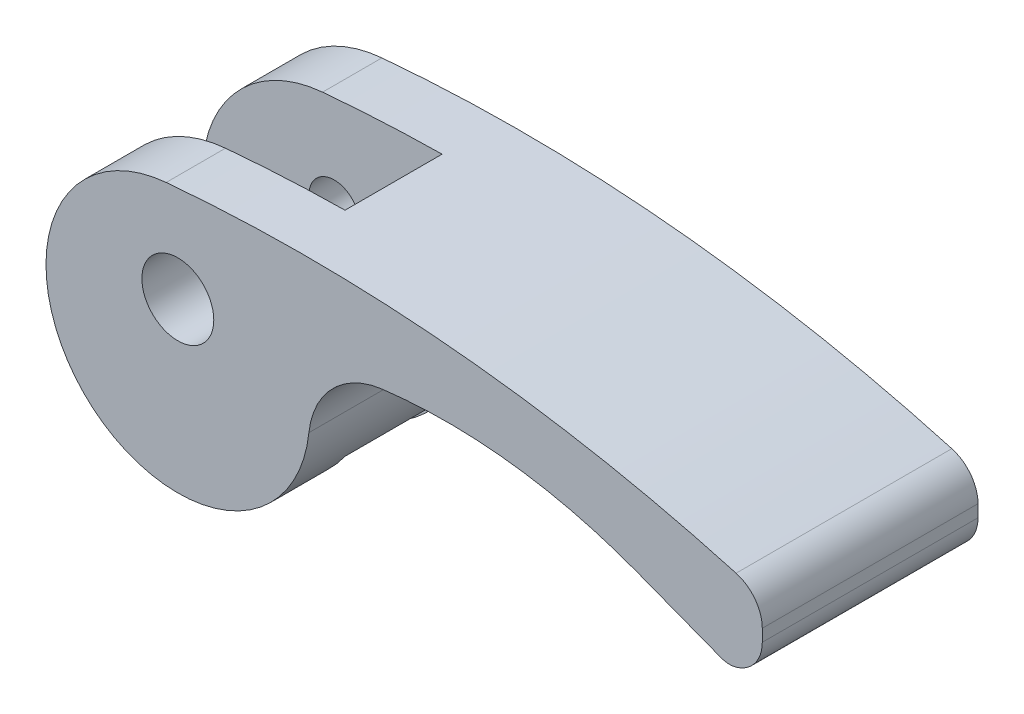
SolidWorks part; units mm, degrees
ref_plane "Спереди" through (0, 0, 0) normal (0, 0, 1) x (1, 0, 0)
ref_plane "Сверху" through (0, 0, 0) normal (0, 1, 0) x (1, 0, 0)
ref_plane "Справа" through (0, 0, 0) normal (1, 0, 0) x (0, 0, -1)
sketch "Эскиз1" plane through (0, 0, 0) normal (0, 0, 1) x (1, 0, 0)
  circle A0 centre (0, 0) radius 11
  dimension "D1" = 22
extrude "Бобышка-Вытянуть1" add sketch "Эскиз1" along normal blind 18
sketch "Эскиз2" plane through (0, 0, 0) normal (0, 0, 1) x (1, 0, 0)
  line L5 (48.7684, 3.611) -> (48.7684, 2.5957)
  line L6 (45.7647, -0.4043) -> (38.3997, 2.4227)
  line L7 (-0.9712, 10.957) -> (10.3662, 3.68)
  circle A3 centre (0, 0) radius 11 construction
  arc A4 (-0.9712, 10.957) -> (46.5842, 6.4979) centre (10.6848, -120.548) cw
  arc A6 (48.7684, 2.5957) -> (45.7647, -0.4043) centre (45.7684, 2.5957) cw
  arc A7 (46.5842, 6.4979) -> (48.7684, 3.611) centre (45.7684, 3.611) cw
  arc A8 (10.3662, 3.68) -> (38.3997, 2.4227) centre (22.4964, -39.0097) cw
  point P13 (48.7684, 5.8604)
  point P23 (48.7684, 5.8604)
  dimension "D2" = 3
  dimension "D3" = 3
  dimension "D1" = 50
extrude "Бобышка-Вытянуть2" add sketch "Эскиз2" along normal up to surface (18 mm away) up to face at (11, 0, 18)
fillet "Скругление1" radius 2 1 edges at (45.7647, -0.4043, 9)
sketch "Эскиз3" plane through (0, 0, 0) normal (0, 1, 0) x (1, 0, 0)
  line L0 (-11, 0) -> (-11, -18) construction
  line L1 (-11, -13.05) -> (9, -13.05)
  line L2 (-11, -13.05) -> (-11, -4.95)
  line L3 (-11, -4.95) -> (9, -4.95)
  line L4 (9, -13.05) -> (9, -4.95)
  line L5 (48.7684, -18) -> (48.7684, 0) construction
  point P6 (9, -9)
  point P9 (48.7684, -9)
  dimension "D1" = 0
  dimension "D2" = 8.1
  dimension "D3" = 20
extrude "Вырез-Вытянуть1" cut sketch "Эскиз3" against normal through all both and the other way through all
sketch "Эскиз4" plane through (0, 0, 18) normal (0, 0, 1) x (1, 0, 0)
  circle A0 centre (0, 3) radius 3
  dimension "D2" = 6
  dimension "D1" = 3
extrude "Вырез-Вытянуть2" cut sketch "Эскиз4" against normal up to surface (4.95 mm away) up to face at (1.1606, 2.7917, 13.05)
sketch "Эскиз5" plane through (0, 0, 18) normal (0, 0, 1) x (1, 0, 0)
  circle A0 centre (0, 3) radius 2.1
  dimension "D1" = 4.2
extrude "Вырез-Вытянуть3" cut sketch "Эскиз5" against normal through all
fillet "Скругление2" radius 7 1 edges at (10.3662, 3.68, 9)
